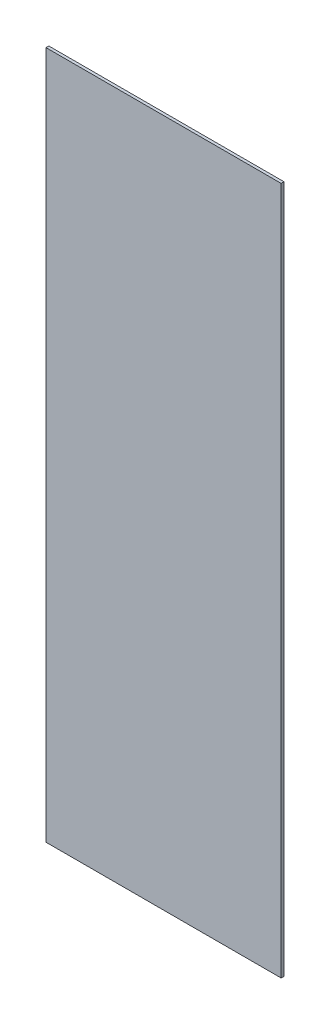
SolidWorks part; units mm, degrees
material "7075-O (SS)"
ref_plane "Front Plane" through (0, 0, 0) normal (0, 0, 1) x (1, 0, 0)
ref_plane "Top Plane" through (0, 0, 0) normal (0, 1, 0) x (1, 0, 0)
ref_plane "Right Plane" through (0, 0, 0) normal (1, 0, 0) x (0, 0, -1)
sketch "Sketch1" plane through (0, 0, 0) normal (0, 0, 1) x (1, 0, 0)
  line L1 (0, 0) -> (83, 0)
  line L2 (0, 0) -> (0, 243)
  line L3 (0, 243) -> (83, 243)
  line L4 (83, 0) -> (83, 243)
  dimension "D1" = 83
  dimension "D2" = 243
extrude "Boss-Extrude1" add sketch "Sketch1" along normal blind 1
